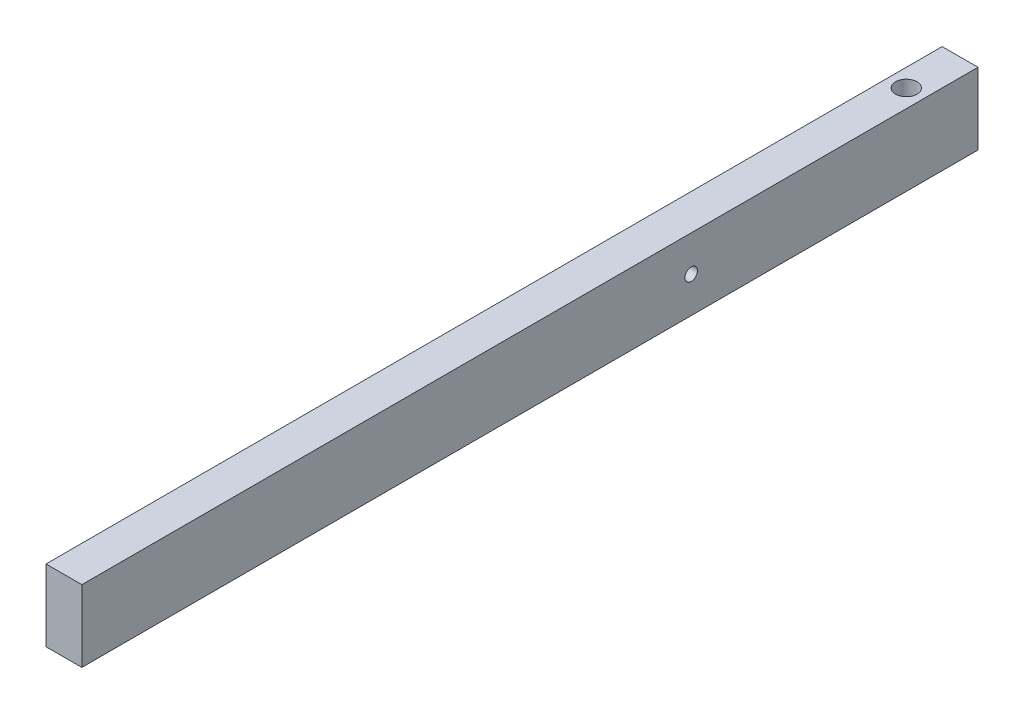
SolidWorks part; units mm, degrees
ref_plane "Спереди" through (0, 0, 0) normal (0, 0, 1) x (1, 0, 0)
ref_plane "Сверху" through (0, 0, 0) normal (0, 1, 0) x (1, 0, 0)
ref_plane "Справа" through (0, 0, 0) normal (1, 0, 0) x (0, 0, -1)
sketch "Эскиз2" plane through (0, 0, 0) normal (0, 0, 1) x (1, 0, 0)
  line L1 (-10, 20) -> (10, 20)
  line L2 (-10, 20) -> (-10, -20)
  line L3 (-10, -20) -> (10, -20)
  line L4 (10, 20) -> (10, -20)
  line L5 (-10, 20) -> (10, -20) construction
  line L6 (-10, -20) -> (10, 20) construction
  point P0 (0, 0)
extrude "Бобышка-Вытянуть6" add sketch "Эскиз2" along normal blind 500
sketch "Эскиз3" plane through (0, 20, 0) normal (0, 1, 0) x (1, 0, 0)
  line L0 (10, 0) -> (-10, 0) construction
  circle A0 centre (0, -30) radius 6
  dimension "D1" = 12
  dimension "D2" = 30
extrude "Вырез-Вытянуть1" cut sketch "Эскиз3" against normal through all
sketch "Эскиз5" plane through (-10, 0, 0) normal (-1, 0, 0) x (0, 0, 1)
  line L0 (0, 20) -> (0, -20) construction
  circle A0 centre (160, 0) radius 3.5
  point P4 (0, 0)
  point P5 (0, 0)
  dimension "D1" = 7
  dimension "D2" = 160
extrude "Вырез-Вытянуть2" cut sketch "Эскиз5" against normal through all
equation "\"r2\"=12"
equation "\"D1@Эскиз3\"=\"r2\""
equation "\"d\"=30"
equation "\"D2@Эскиз3\"=\"d\""
equation "\"f1\"=7"
equation "\"D1@Эскиз5\"=\"f1\""
